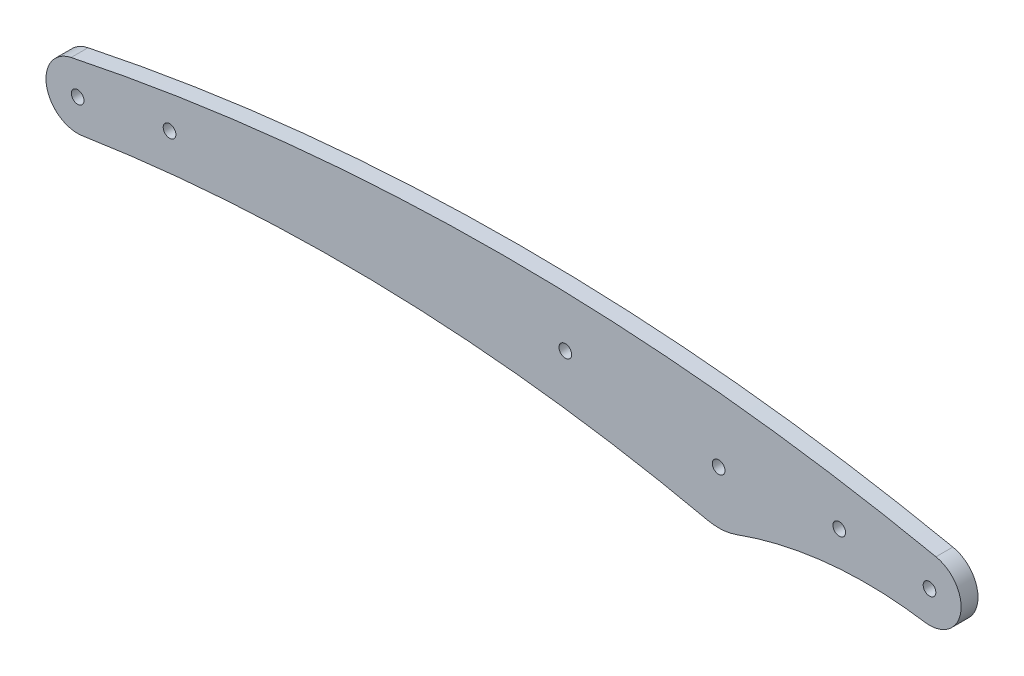
SolidWorks part; units mm, degrees
material "Acrílico (Impacto medio-alto)"
ref_plane "Piano frontale" through (0, 0, 0) normal (0, 0, 1) x (1, 0, 0)
ref_plane "Piano superiore" through (0, 0, 0) normal (0, 1, 0) x (1, 0, 0)
ref_plane "Piano destro" through (0, 0, 0) normal (1, 0, 0) x (0, 0, -1)
sketch "Schizzo1" plane through (0, 0, 0) normal (0, 0, 1) x (1, 0, 0)
  line L0 (0, 0) -> (152, 0) construction
  line L1 (152, 0) -> (202, 0) construction
  circle A0 centre (0, 0) radius 1.5
  circle A1 centre (202, 0) radius 1.5
  arc A2 (-1.5381, 7.3406) -> (1.1505, -7.4112) centre (0, 0) ccw
  arc A3 (200.8462, -7.4107) -> (203.5381, 7.3406) centre (202, 0) ccw
  circle A4 centre (152, 0) radius 1.5
  arc A5 (149.2883, -12.2023) -> (156.2683, -11.7487) centre (152, 0) ccw
  arc A6 (149.2883, -12.2023) -> (1.1505, -7.4112) centre (62.5132, -402.6765) ccw
  arc A7 (203.5381, 7.3406) -> (-1.5381, 7.3406) centre (101, -482.0324) ccw
  arc A8 (200.8462, -7.4107) -> (156.2683, -11.7487) centre (187, -96.3392) ccw
  dimension "D1" = 3
  dimension "D2" = 3
  dimension "D4" = 15
  dimension "D5" = 15
  dimension "D6" = 3
  dimension "D8" = 25
  dimension "D9" = 800
  dimension "D10" = 1000
  dimension "D11" = 152
  dimension "D12" = 90
  dimension "D3" = 202
extrude "Estrusione-Estrusione1" add sketch "Schizzo1" along normal blind 4
sketch "Schizzo2" plane through (0, 0, 4) normal (0, 0, 1) x (1, 0, 0)
  circle A0 centre (21.7926, 3.9239) radius 1.5
  circle A1 centre (115.6435, 5.6739) radius 1.5
  circle A2 centre (180.6026, 1.5866) radius 1.5
  dimension "D1" = 3
  dimension "D2" = 3
  dimension "D3" = 3
extrude "Taglio-Estrusione1" cut sketch "Schizzo2" against normal blind 10
